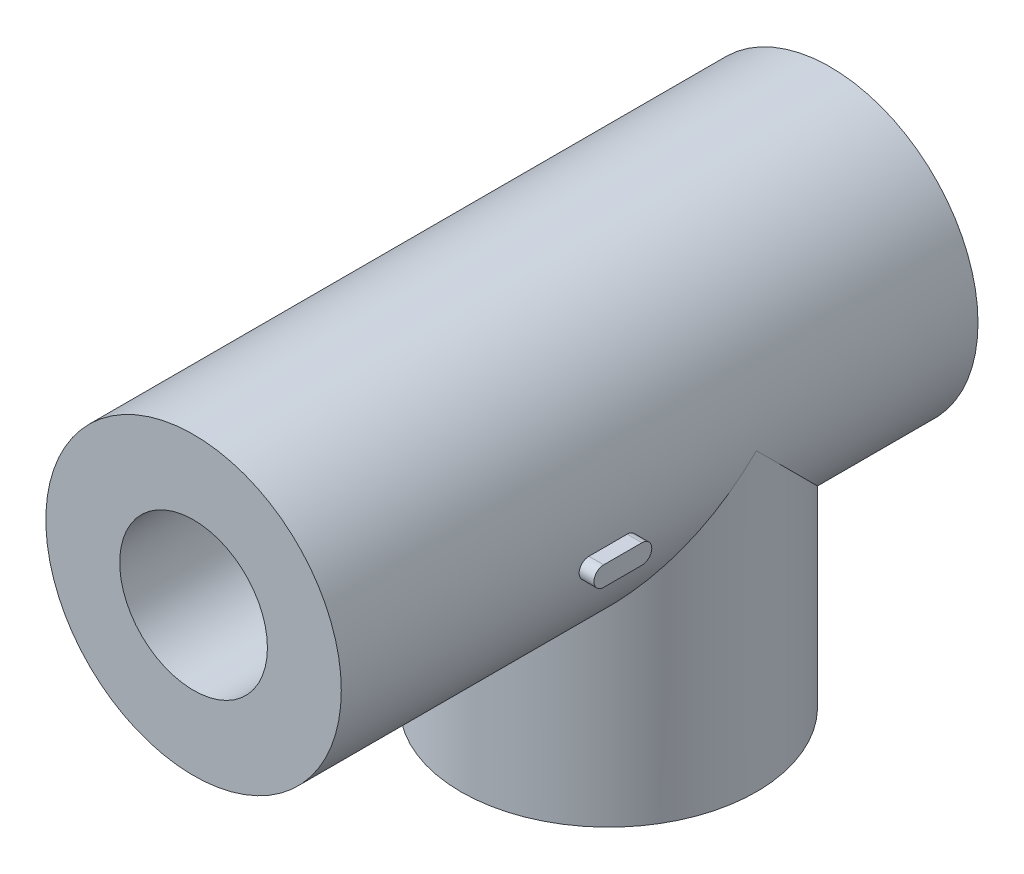
SolidWorks part; units mm, degrees
material "6061-T6 (SS)"
ref_plane "Front Plane" through (0, 0, 0) normal (0, 0, 1) x (1, 0, 0)
ref_plane "Top Plane" through (0, 0, 0) normal (0, 1, 0) x (1, 0, 0)
ref_plane "Right Plane" through (0, 0, 0) normal (1, 0, 0) x (0, 0, -1)
sketch "Sketch1" plane through (0, 0, 0) normal (0, 0, 1) x (1, 0, 0)
  circle A0 centre (0, 0) radius 20
extrude "Boss-Extrude1" add sketch "Sketch1" along normal blind 86.2
sketch "Sketch3" plane through (0, 0, 0) normal (1, 0, 0) x (0, 0, -1)
  line L0 (-86.2, 0) -> (-30, 0) construction
  line L1 (-86.2, 20) -> (-86.2, -20) construction
sketch "Sketch4" plane through (0, 0, 0) normal (0, 1, 0) x (1, 0, 0)
  line L0 (0, -86.2) -> (0, -30) construction
  circle A0 centre (0, -30) radius 20
extrude "Boss-Extrude2" add sketch "Sketch4" against normal blind 40
sketch "Sketch5" plane through (0, -40, 0) normal (0, -1, 0) x (1, 0, 0)
  circle A2 centre (0, 30) radius 10
extrude "Cut-Extrude1" cut sketch "Sketch5" against normal blind 20
sketch "Sketch6" plane through (0, 0, 86.2) normal (0, 0, 1) x (1, 0, 0)
  circle A0 centre (0, 0) radius 10
extrude "Cut-Extrude2" cut sketch "Sketch6" against normal blind 20
ref_plane "Plane1" through (20, 0, 0) normal (1, 0, 0) x (0, 0, -1)
sketch "Sketch7" plane through (20, 0, 0) normal (1, 0, 0) x (0, 0, -1)
  line L0 (-52.6751, -2.3588) -> (-47.4866, -2.3588) construction
  line L1 (-52.6751, -1.0381) -> (-47.4866, -1.0381)
  line L2 (-52.6751, -3.6795) -> (-47.4866, -3.6795)
  arc A0 (-52.6751, -1.0381) -> (-52.6751, -3.6795) centre (-52.6751, -2.3588) ccw
  arc A1 (-47.4866, -3.6795) -> (-47.4866, -1.0381) centre (-47.4866, -2.3588) ccw
  point P2 (-50.0809, -2.3588)
extrude "Boss-Extrude3" add sketch "Sketch7" along normal blind 2 separate body
ref_plane "Plane2" through (0, 0, 0) normal (1, 0, 0) x (0, 0, -1)
sketch "Sketch8" plane through (0, 0, 0) normal (1, 0, 0) x (0, 0, -1)
  line L0 (-86.2, 0) -> (-30, 0) construction
  line L1 (-86.2, 20) -> (-86.2, -20) construction
  line L2 (-30, -40) -> (-30, 0) construction
  line L3 (-50, -40) -> (-10, -40) construction
  line L4 (-50, -20) -> (-30, 0) construction
